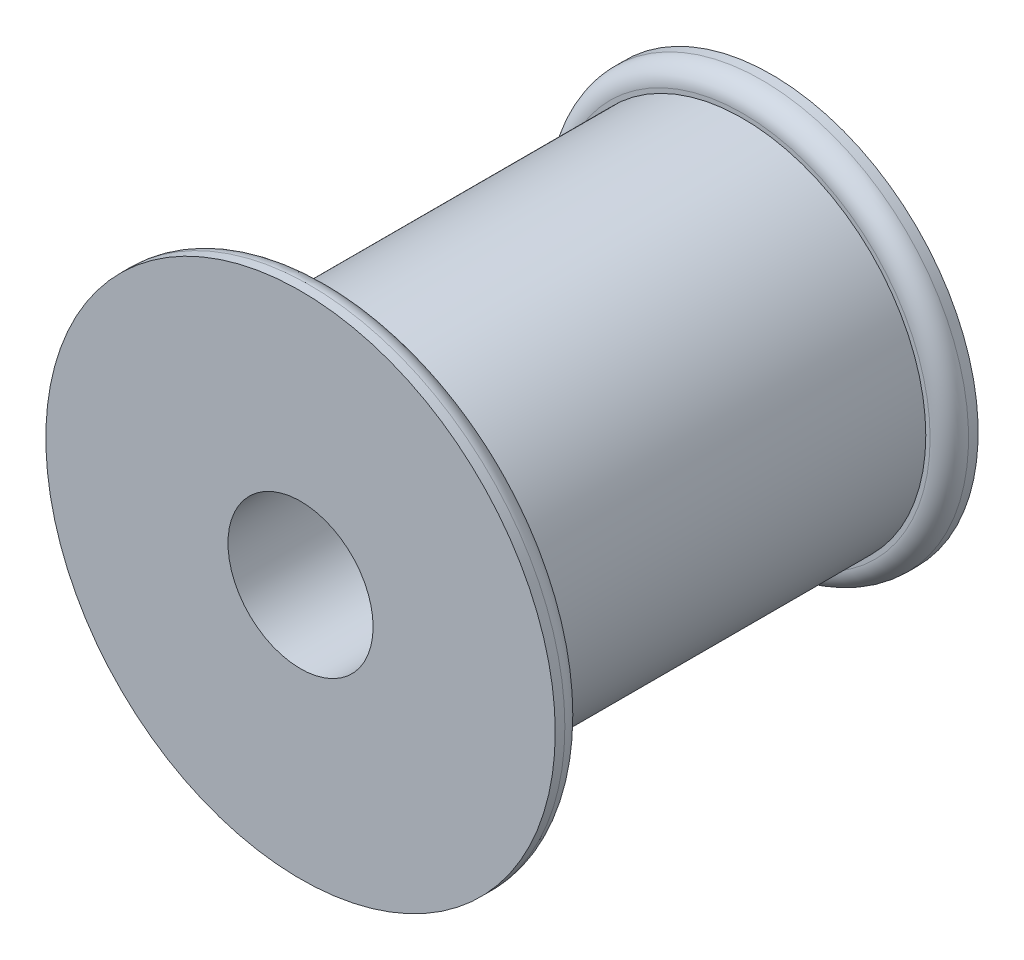
SolidWorks part; units mm, degrees
ref_plane "Front Plane" through (0, 0, 0) normal (0, 0, 1) x (1, 0, 0)
ref_plane "Top Plane" through (0, 0, 0) normal (0, 1, 0) x (1, 0, 0)
ref_plane "Right Plane" through (0, 0, 0) normal (1, 0, 0) x (0, 0, -1)
sketch "Sketch1" plane through (0, 0, 0) normal (0, 0, 1) x (1, 0, 0)
  circle A0 centre (0, 0) radius 4.14
  circle A1 centre (0, 0) radius 19.05
  dimension "D1" = 8.28
  dimension "D2" = 38.1
extrude "Boss-Extrude1" add sketch "Sketch1" along normal blind 43
sketch "Sketch2" plane through (0, 0, 43) normal (0, 0, 1) x (1, 0, 0)
  circle A0 centre (0, 0) radius 26.5
  dimension "D1" = 53
extrude "Boss-Extrude2" add sketch "Sketch2" along normal blind 3
sketch "Sketch3" plane through (0, 0, 0) normal (0, 0, -1) x (-1, 0, 0)
  circle A0 centre (0, 0) radius 21.5
  circle A1 centre (0, 0) radius 4.14
  dimension "D1" = 43
  dimension "D2" = 8.28
extrude "Boss-Extrude3" add sketch "Sketch3" along normal blind 3
sketch "Sketch4" plane through (0, 0, 46) normal (0, 0, 1) x (1, 0, 0)
  circle A0 centre (0, 0) radius 7.55
  dimension "D1" = 15.1
extrude "Cut-Extrude1" cut sketch "Sketch4" against normal blind 15
fillet "Fillet1" radius 2 1 edges at (26.5, 0, 43)
fillet "Fillet2" radius 2 1 edges at (-21.5, 0, 0)
